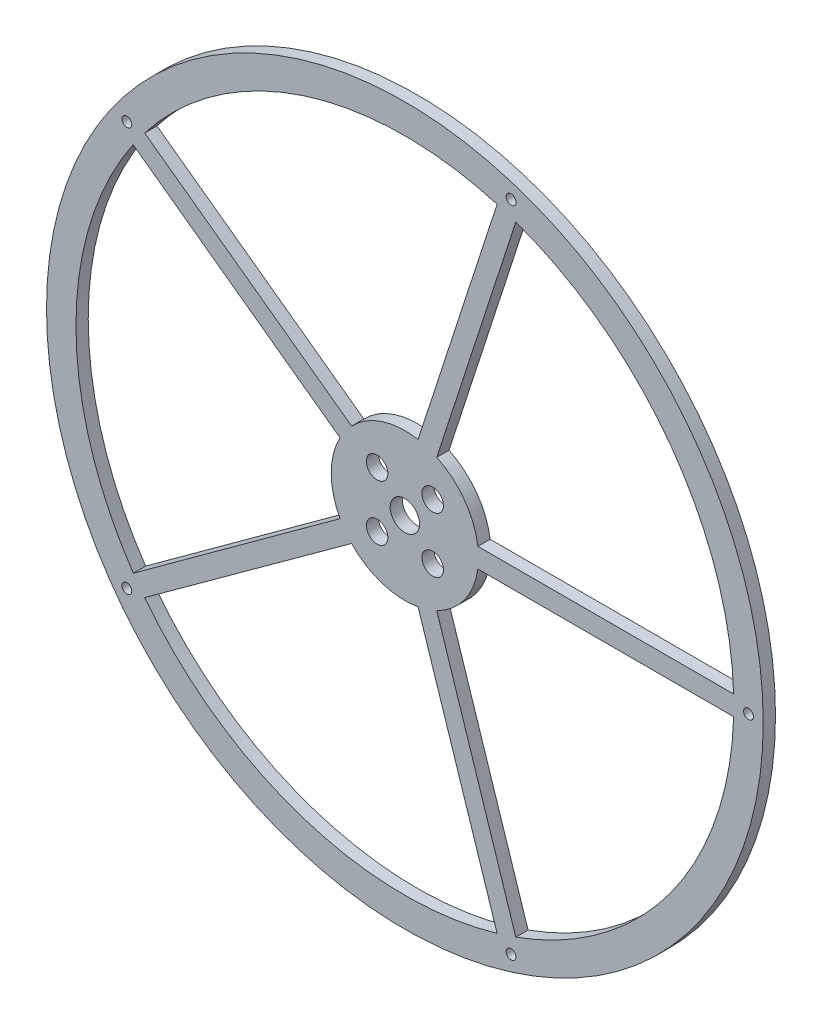
SolidWorks part; units mm, degrees
ref_plane "前视基准面" through (0, 0, 0) normal (0, 0, 1) x (1, 0, 0)
ref_plane "上视基准面" through (0, 0, 0) normal (0, 1, 0) x (1, 0, 0)
ref_plane "右视基准面" through (0, 0, 0) normal (1, 0, 0) x (0, 0, -1)
other "Configuration Table"
sketch "草图3" plane through (0, 0, 0) normal (0, 0, 1) x (1, 0, 0)
  circle A0 centre (0, 0) radius 73
extrude "凸台-拉伸3" add sketch "草图3" along normal blind 2.5
sketch "草图5" plane through (0, 0, 2.5) normal (0, 0, 1) x (1, 0, 0)
  circle A0 centre (0, 0) radius 67
extrude "切除-拉伸1" cut sketch "草图5" against normal blind 2.5
sketch "草图6" plane through (0, 0, 2.5) normal (0, 0, 1) x (1, 0, 0)
  circle A0 centre (0, 0) radius 15
extrude "凸台-拉伸4" add sketch "草图6" against normal blind 2.5 separate body
sketch "草图7" plane through (0, 0, 2.5) normal (0, 0, 1) x (1, 0, 0)
  circle A0 centre (0, 0) radius 8
extrude "切除-拉伸2" cut sketch "草图7" against normal blind 2.5
sketch "草图9" plane through (0, 0, 2.5) normal (0, 0, 1) x (1, 0, 0)
  line L0 (0, 0) -> (0, 2)
  line L1 (0, 2) -> (66.9701, 2)
  line L2 (0, 0) -> (0, -2)
  line L3 (0, -2) -> (66.9701, -2)
  line L4 (0, -2) -> (0, 2)
  circle A0 centre (0, 0) radius 67 construction
  arc A1 (66.9701, 2) -> (66.9701, -2) centre (0, 0) cw
  circle M1 centre (0, 0) radius 67
extrude "凸台-拉伸6" add sketch "草图9" against normal blind 2.5 contours L2 L3 L1 L0 M1
sketch "草图10" plane through (0, 0, 2.5) normal (0, 0, 1) x (1, 0, 0)
  line L0 (1.9021, -0.618) -> (0, 0)
  line L1 (0, 0) -> (-1.9021, 0.618)
  line L2 (1.9021, -0.618) -> (22.597, 63.0744)
  line L3 (-1.9021, 0.618) -> (18.7928, 64.3104)
  arc A0 (66.9701, 2) -> (66.9701, -2) centre (0, 0) ccw construction
  arc A1 (18.7928, 64.3104) -> (22.597, 63.0744) centre (0, 0) cw
extrude "凸台-拉伸7" add sketch "草图10" against normal blind 2.5
sketch "草图11" plane through (0, 0, 2.5) normal (0, 0, 1) x (1, 0, 0)
  line L1 (0, 0) -> (1.1756, 1.618)
  line L2 (0, 0) -> (-1.1756, -1.618)
  line L3 (-1.1756, -1.618) -> (-55.3556, 37.746)
  line L4 (1.1756, 1.618) -> (-53.0044, 40.9821)
  arc A0 (18.7928, 64.3104) -> (66.9701, -2) centre (0, 0) ccw construction
  arc A1 (-55.3556, 37.746) -> (-53.0044, 40.9821) centre (0, 0) cw
extrude "凸台-拉伸8" add sketch "草图11" against normal blind 2.5
sketch "草图12" plane through (0, 0, 2.5) normal (0, 0, 1) x (1, 0, 0)
  line L1 (0, 0) -> (1.1756, -1.618)
  line L2 (0, 0) -> (-1.1756, 1.618)
  line L3 (1.1756, -1.618) -> (-53.0044, -40.9821)
  line L4 (-1.1756, 1.618) -> (-55.303, -37.8229)
  arc A0 (-55.3556, 37.746) -> (66.9701, -2) centre (0, 0) ccw construction
  arc A1 (-55.303, -37.8229) -> (-53.0044, -40.9821) centre (0, 0) ccw
extrude "凸台-拉伸9" add sketch "草图12" against normal blind 2.5
sketch "草图13" plane through (0, 0, 2.5) normal (0, 0, 1) x (1, 0, 0)
  line L1 (0, 0) -> (1.9021, 0.618)
  line L2 (1.9021, 0.618) -> (22.597, -63.0744)
  line L3 (0, 0) -> (-1.9021, -0.618)
  line L4 (-1.9021, -0.618) -> (18.7928, -64.3104)
  arc A0 (-53.0044, -40.9821) -> (66.9701, -2) centre (0, 0) ccw construction
  arc A1 (22.597, -63.0744) -> (18.7928, -64.3104) centre (0, 0) cw
extrude "凸台-拉伸10" add sketch "草图13" against normal blind 2.5
sketch "草图14" plane through (0, 0, 2.5) normal (0, 0, 1) x (1, 0, 0)
  circle A0 centre (0, 0) radius 8
extrude "切除-拉伸3" cut sketch "草图14" against normal blind 2.5
sketch "草图15" plane through (0, 0, 2.5) normal (0, 0, 1) x (1, 0, 0)
  circle A0 centre (70, 0) radius 1
  circle A1 centre (21.6312, 66.574) radius 1
  circle A2 centre (-56.6312, 41.145) radius 1
  circle A3 centre (-56.6312, -41.145) radius 1
  circle A4 centre (21.6312, -66.574) radius 1
extrude "切除-拉伸4" cut sketch "草图15" against normal blind 2.5
sketch "草图16" plane through (0, 0, 2.5) normal (0, 0, 1) x (1, 0, 0)
  circle A0 centre (0, 0) radius 8
extrude "凸台-拉伸11" add sketch "草图16" against normal blind 2.5
sketch "草图17" plane through (0, 0, 2.5) normal (0, 0, 1) x (1, 0, 0)
  circle A0 centre (0, 0) radius 3
extrude "切除-拉伸5" cut sketch "草图17" against normal blind 2.5
sketch "草图18" plane through (0, 0, 2.5) normal (0, 0, 1) x (1, 0, 0)
  circle A0 centre (5.657, 5.657) radius 3.25
  circle A1 centre (-5.657, -5.657) radius 3.25
  circle A2 centre (5.657, -5.657) radius 2.2
  circle A3 centre (-5.657, 5.657) radius 2.2
extrude "切除-拉伸6" cut sketch "草图18" against normal blind 2.5
sketch "草图19" plane through (0, 0, 2.5) normal (0, 0, 1) x (1, 0, 0)
  circle A0 centre (5.657, 5.657) radius 3.25
  circle A1 centre (-5.657, -5.657) radius 3.25
extrude "凸台-拉伸12" add sketch "草图19" against normal blind 2.5
sketch "草图20" plane through (0, 0, 2.5) normal (0, 0, 1) x (1, 0, 0)
  circle A0 centre (5.657, 5.657) radius 2.2
  circle A1 centre (-5.657, -5.657) radius 2.2
extrude "切除-拉伸7" cut sketch "草图20" against normal blind 2.5
